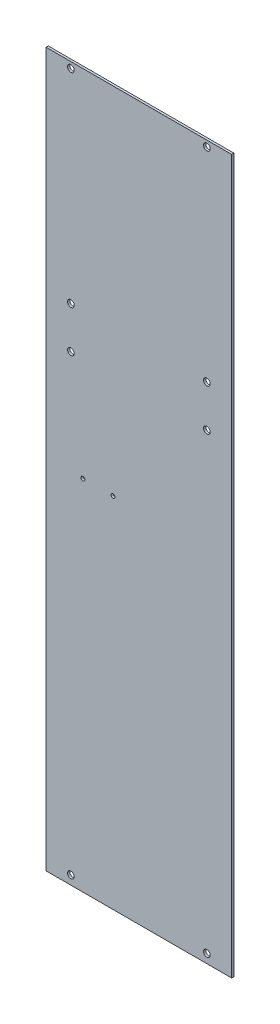
SolidWorks part; units mm, degrees
material "CFRP"
ref_plane "Front Plane" through (0, 0, 0) normal (0, 0, 1) x (1, 0, 0)
ref_plane "Top Plane" through (0, 0, 0) normal (0, 1, 0) x (1, 0, 0)
ref_plane "Right Plane" through (0, 0, 0) normal (1, 0, 0) x (0, 0, -1)
sketch "Sketch1" plane through (0, 0, 0) normal (0, 0, 1) x (1, 0, 0)
  line L1 (41.6, -160) -> (-41.6, -160)
  line L2 (41.6, -160) -> (41.6, 160)
  line L3 (41.6, 160) -> (-41.6, 160)
  line L4 (-41.6, -160) -> (-41.6, 160)
  line L5 (41.6, -160) -> (-41.6, 160) construction
  line L6 (41.6, 160) -> (-41.6, -160) construction
  point P0 (0, 0)
  dimension "D1" = 83.2
  dimension "D2" = 320
extrude "Boss-Extrude1" add sketch "Sketch1" along normal blind 1
hole_wizard "Ø3.0 (3) Diameter Hole1" positions "Sketch3" profile "Sketch2" hole size "Ø3.0" standard "ANSI Metric"
sketch "Sketch3" plane through (0, 0, 1) normal (0, 0, 1) x (1, 0, 0)
  line L6 (-41.6, -160) -> (41.6, -160) construction
  line L9 (41.6, 160) -> (-41.6, 160) construction
  line L10 (0, 160) -> (0, 163.7587) construction
  line L11 (0, 160) -> (0, -152.1509) construction
  point P0 (-30.5, 66)
  point P2 (30.5, 66)
  point P15 (30.5, -156)
  point P17 (-30.5, -156)
  point P54 (-30.5, 157.3)
  point P56 (30.5, 157.3)
  point P58 (-30.5, 47.3)
  point P60 (30.5, 47.3)
  dimension "D2" = 4
  dimension "D3" = 2.7
  dimension "D4" = 4
  dimension "D5" = 30.5
  dimension "D6" = 30.5
  dimension "D7" = 94
  dimension "D8" = 30.5
  dimension "D9" = 2.7
  dimension "D10" = 94
  dimension "D11" = 30.5
  dimension "D12" = 30.5
  dimension "D13" = 30.5
  dimension "D14" = 30.5
  dimension "D15" = 30.5
  dimension "D16" = 112.7
  dimension "D17" = 112.7
sketch "Sketch2" plane through (-30.5, 66, 1) normal (1, 0, 0) x (0, -1, 0)
  line L0 (0, 0) -> (0, 1)
  line L1 (0, 1) -> (1.5, 1)
  line L2 (1.5, 1) -> (1.5, 0)
  line L5 (1.5, 0) -> (0, 0)
  line L10 (0, 1) -> (-1.5, 1) construction
  line L11 (0, -6.35) -> (0, 107.95) construction
  dimension "Hole Dia." = 3
  dimension "Hole Depth" = 1
  dimension "Drill Angle" = 180
hole_wizard "Ø1.75 (1.75) Diameter Hole1" positions "Sketch6" profile "Sketch5" hole size "Ø1.75" standard "ANSI Metric" end condition through all
sketch "Sketch6" plane through (0, 0, 1) normal (0, 0, 1) x (1, 0, 0)
  point P0 (-25.1, 0.65)
  point P3 (-11.6, 0.65)
sketch "Sketch5" plane through (-25.1, 0.65, 1) normal (1, 0, 0) x (0, -1, 0)
  line L0 (0, 0) -> (0, 1)
  line L1 (0, 1) -> (0.875, 1)
  line L2 (0.875, 1) -> (0.875, 0)
  line L5 (0.875, 0) -> (0, 0)
  line L11 (0, -6.35) -> (0, 107.95) construction
  dimension "Thru Hole Dia." = 1.75
  dimension "Thru Hole Depth" = 1
